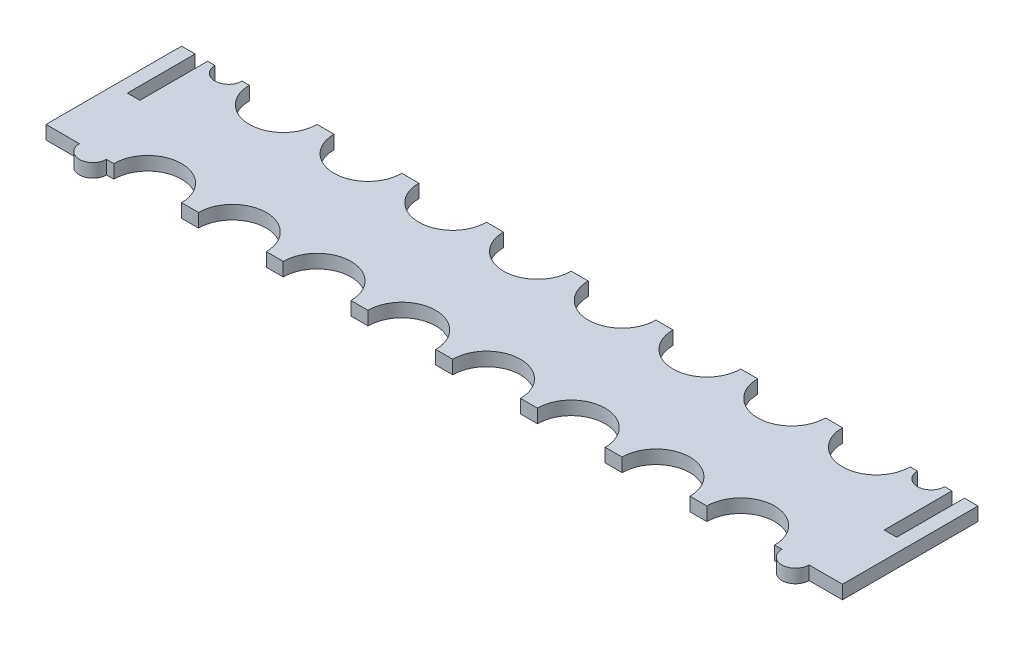
SolidWorks part; units mm, degrees
ref_plane "Front Plane" through (0, 0, 0) normal (0, 0, 1) x (1, 0, 0)
ref_plane "Top Plane" through (0, 0, 0) normal (0, 1, 0) x (1, 0, 0)
ref_plane "Right Plane" through (0, 0, 0) normal (1, 0, 0) x (0, 0, -1)
sketch "Sketch1" plane through (0, 0, 0) normal (0, 1, 0) x (1, 0, 0)
  line L1 (0, 0) -> (235, 0)
  line L2 (0, 0) -> (0, 40)
  line L3 (0, 40) -> (235, 40)
  line L4 (235, 0) -> (235, 40)
  dimension "D1" = 40
  dimension "D2" = 235
extrude "Boss-Extrude1" add sketch "Sketch1" along normal blind 4
sketch "Sketch2" plane through (0, 4, 0) normal (0, 1, 0) x (1, 0, 0)
  line L0 (235, 40) -> (0, 40) construction
  line L1 (4, 40) -> (7.7, 40)
  line L2 (4, 40) -> (4, 20)
  line L3 (4, 20) -> (7.7, 20)
  line L4 (7.7, 40) -> (7.7, 20)
  line L5 (0, 40) -> (0, 0) construction
  line L6 (117.5, 40) -> (117.5, 63.0985) construction
  line L7 (227.3, 40) -> (227.3, 20)
  line L8 (231, 20) -> (227.3, 20)
  line L9 (231, 40) -> (231, 20)
  line L10 (231, 40) -> (227.3, 40)
  dimension "D1" = 4
  dimension "D2" = 20
  dimension "D3" = 3.7
extrude "Cut-Extrude1" cut sketch "Sketch2" against normal blind 4
sketch "Sketch3" plane through (0, 4, 0) normal (0, 1, 0) x (1, 0, 0)
  line L0 (227.3, 40) -> (7.7, 40) construction
  line L1 (0, 40) -> (0, 0) construction
  circle A0 centre (30, 40) radius 10
  dimension "D1" = 20
  dimension "D2" = 30
extrude "Cut-Extrude2" cut sketch "Sketch3" against normal blind 4
pattern_linear "LPattern1" count 8 spacing 25 along (1, 0, 0) of "Cut-Extrude2"
sketch "Sketch4" plane through (0, 4, 0) normal (0, 1, 0) x (1, 0, 0)
  line L0 (227.3, 40) -> (215, 40) construction
  line L1 (117.5, 0) -> (117.5, 42.5527) construction
  line L2 (0, 0) -> (235, 0) construction
  circle A0 centre (221.15, 40) radius 4
  circle A1 centre (13.85, 40) radius 4
  dimension "D1" = 8
extrude "Cut-Extrude3" cut sketch "Sketch4" against normal blind 4
sketch "Sketch5" plane through (0, 4, 0) normal (0, 1, 0) x (1, 0, 0)
  line L0 (221.15, 40) -> (221.15, -7.0446) construction
  line L1 (0, 0) -> (235, 0) construction
  line L2 (117.5, 0) -> (117.5, -18.4358) construction
  circle A0 centre (221.15, 0) radius 4
  circle A1 centre (13.85, 0) radius 4
  dimension "D1" = 8
extrude "Boss-Extrude2" add sketch "Sketch5" against normal blind 4
ref_plane "Plane1" through (0, 0, -20) normal (0, 0, -1) x (-1, 0, 0)
mirror "Mirror1" about plane through (0, 0, -20) normal (0, 0, -1) of "LPattern1", "Cut-Extrude2"
